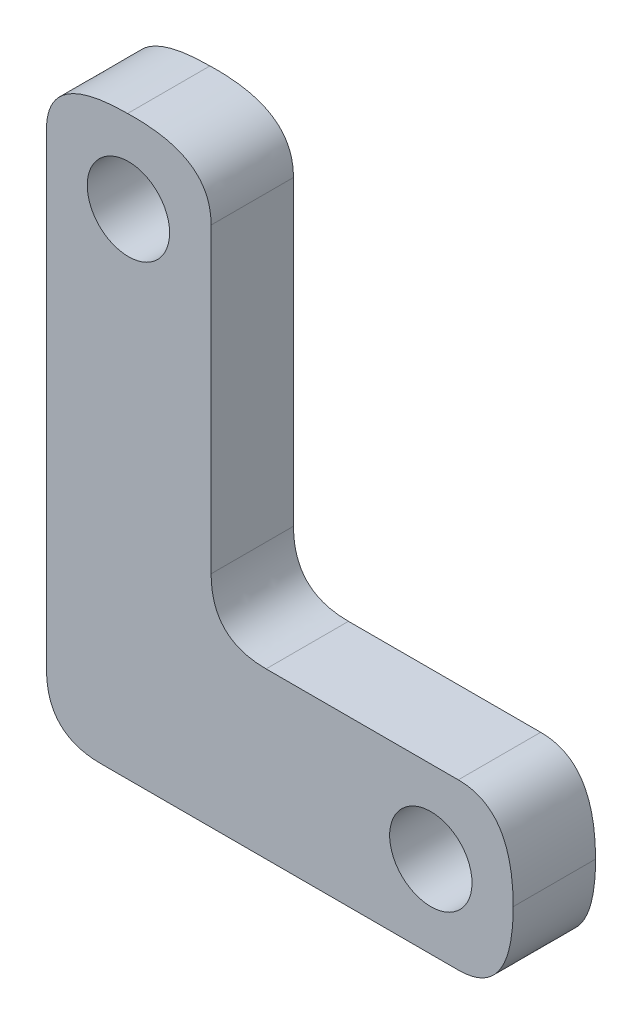
SolidWorks part; units mm, degrees
ref_plane "Plan de face" through (0, 0, 0) normal (0, 0, 1) x (1, 0, 0)
ref_plane "Plan de dessus" through (0, 0, 0) normal (0, 1, 0) x (1, 0, 0)
ref_plane "Plan de droite" through (0, 0, 0) normal (1, 0, 0) x (0, 0, -1)
sketch "Esquisse1" plane through (0, 0, 0) normal (0, 0, 1) x (1, 0, 0)
  line L0 (0, -7.9656) -> (0, 5.2165) construction
  line L1 (-3.7569, 0) -> (18.7817, 0) construction
  line L2 (2, 0) -> (15.0001, 0)
  line L3 (0, 2) -> (0, 19)
  line L5 (6, 19) -> (6, 8)
  line L6 (8, 6) -> (15, 6)
  line L8 (0, 19) -> (0, 20.9946) construction
  line L9 (0, 20.9946) -> (2.9553, 20.9946) construction
  line L10 (2.9553, 20.9946) -> (5.9912, 21.0798) construction
  line L11 (5.9912, 21.0798) -> (6, 19) construction
  line L12 (0, 19) -> (6, 19) construction
  line L13 (6, 8) -> (6, 6) construction
  line L14 (6, 6) -> (8, 6) construction
  line L15 (0, 2) -> (0, 0) construction
  line L16 (0, 0) -> (2, 0) construction
  line L17 (15, 6) -> (17, 6) construction
  line L18 (17, 6) -> (17, 3) construction
  line L19 (15.0001, 0) -> (17, 0) construction
  line L20 (17, 0) -> (17, 3) construction
  line L21 (15, 6) -> (15.0001, 0) construction
  line L22 (6, 8) -> (-0.3189, 8) construction
  line L23 (8, 6) -> (8, -1.3942) construction
  line L24 (0, 2) -> (3.6858, 2) construction
  line L25 (2, 0) -> (2, 3.3021) construction
  circle A0 centre (14, 3) radius 1.5
  circle A1 centre (2.9859, 17.9947) radius 1.5
  spline S0 degree 2 poles (0, 19) (0, 20.9946) (2.9553, 20.9946) knots 0 0 0 1 1 1
  spline S1 degree 2 poles (2.9553, 20.9946) (5.9912, 21.0798) (6, 19) knots 0 0 0 1 1 1
  spline S2 degree 2 poles (6, 8) (6, 6) (8, 6) knots 0 0 0 1 1 1
  spline S3 degree 2 poles (0, 2) (0, 0) (2, 0) knots 0 0 0 1 1 1
  spline S4 degree 2 poles (15, 6) (17, 6) (17, 3) knots 0 0 0 1 1 1
  spline S5 degree 2 poles (15.0001, 0) (17, 0) (17, 3) knots 0 0 0 1 1 1
  point P2 (0, 19)
  point P5 (6, 19)
  point P8 (0, 0)
  point P9 (6, 8)
  point P11 (8, 6)
  point P17 (15, 6)
  point P19 (15.0001, 0)
  point P20 (0, 2)
  point P21 (2, 0)
  point P37 (0, 0)
  point P38 (0, 0)
  point P39 (0, 0)
  point P40 (3.0054, 15.9593)
  point P41 (0, 0)
  point P42 (5.9912, 21.0798)
  point P43 (0, 20.9946)
  point P44 (2.9859, 20.9946)
  point P45 (0, 0)
  dimension "D1" = 3
  dimension "D3" = 3
  dimension "D2" = 3
  dimension "D4" = 3
  dimension "D5" = 17
extrude "Boss.-Extru.1" add sketch "Esquisse1" along normal blind 3
